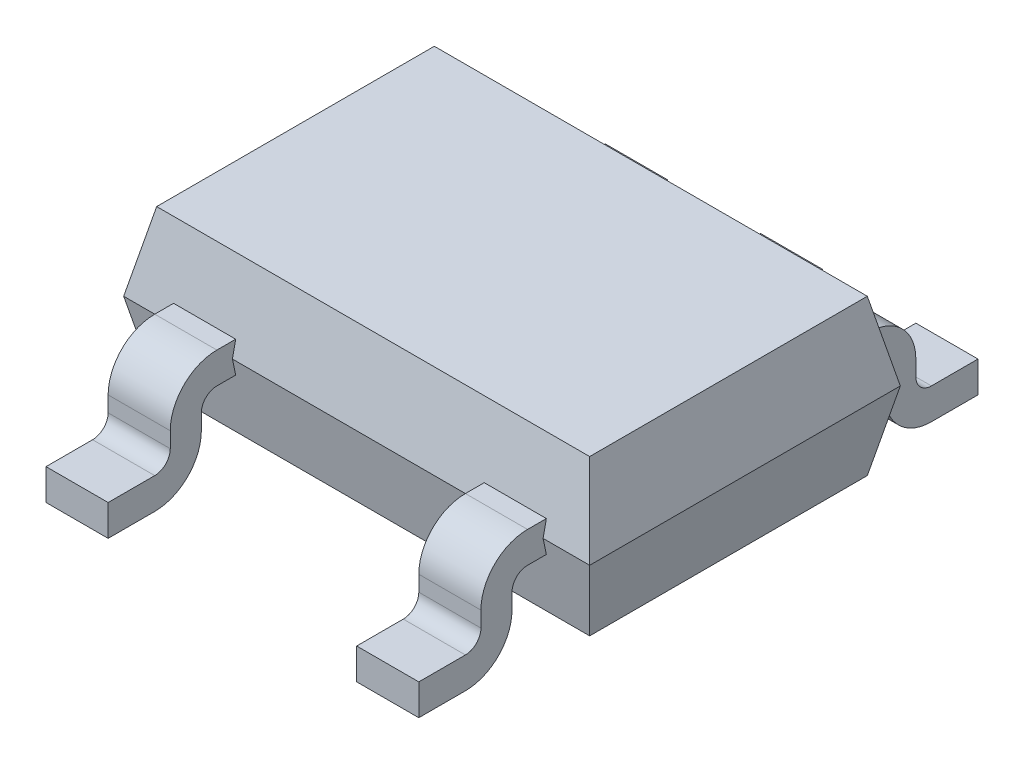
SolidWorks part; units mm, degrees
ref_plane "Front Plane" through (0, 0, 0) normal (0, 0, 1) x (1, 0, 0)
ref_plane "Top Plane" through (0, 0, 0) normal (0, 1, 0) x (1, 0, 0)
ref_plane "Right Plane" through (0, 0, 0) normal (1, 0, 0) x (0, 0, -1)
sketch "BaseS" plane through (0, 0, 0) normal (0, 1, 0) x (1, 0, 0)
  line L1 (-1.5, 1) -> (1.5, 1)
  line L2 (-1.5, 1) -> (-1.5, -1)
  line L3 (-1.5, -1) -> (1.5, -1)
  line L4 (1.5, 1) -> (1.5, -1)
  line L5 (-1.5, 1) -> (1.5, -1) construction
  line L6 (-1.5, -1) -> (1.5, 1) construction
  point P0 (0, 0)
  dimension "Width" = 3
  dimension "Length" = 2
extrude "Base" add sketch "BaseS" along normal mid plane 1 draft 12
sketch "VInSolderJointS" plane through (0, 0, 0) normal (1, 0, 0) x (0, 0, -1)
  line L0 (0.9, 0) -> (1.1, 0)
  line L1 (1.3, -0.2) -> (1.3, -0.3)
  line L2 (1.5, -0.5) -> (1.8, -0.5)
  line L3 (-0.8937, -0.5) -> (0.8937, -0.5) construction
  line L4 (0, -0.5) -> (0, 0) construction
  line L5 (-0.8937, -0.5) -> (0.8937, -0.5) construction
  line L6 (-1.5, -0.5) -> (-1.8, -0.5) construction
  line L7 (-1.3, -0.2) -> (-1.3, -0.3) construction
  line L8 (-0.9, 0) -> (-1.1, 0) construction
  arc A0 (1.1, 0) -> (1.3, -0.2) centre (1.1, -0.2) cw
  arc A1 (1.5, -0.5) -> (1.3, -0.3) centre (1.5, -0.3) cw
  arc A2 (-1.5, -0.5) -> (-1.3, -0.3) centre (-1.5, -0.3) ccw construction
  arc A3 (-1.1, 0) -> (-1.3, -0.2) centre (-1.1, -0.2) ccw construction
  point P3 (0, 0)
  dimension "Radius" = 0.2
  dimension "InnerLength" = 0.1
  dimension "TopOuterLength" = 0.1
  dimension "BottomLength" = 0.3
extrude "VInSolderJoint" add sketch "VInSolderJointS" along normal mid plane 0.4 thin thin type mid plane wall 0.2
pattern_linear "SJLP" count 2 spacing 1 along (1, 0, 0) count 2 spacing 1 along (-1, 0, 0) of "VInSolderJoint"
ref_plane "Plane1" through (1, 0, 0) normal (1, 0, 0) x (0, 0, -1)
sketch "VOutSolderJointS" plane through (1, 0, 0) normal (1, 0, 0) x (0, 0, -1)
  line L0 (-1.5, -0.5) -> (-1.8, -0.5) construction
  line L1 (-1.3, -0.2) -> (-1.3, -0.3) construction
  line L2 (-0.9, 0) -> (-1.1, 0) construction
  line L3 (-1.5, -0.5) -> (-1.8, -0.5)
  line L4 (-1.3, -0.2) -> (-1.3, -0.3)
  line L5 (-0.9, 0) -> (-1.1, 0)
  arc A0 (-1.5, -0.5) -> (-1.3, -0.3) centre (-1.5, -0.3) ccw construction
  arc A1 (-1.1, 0) -> (-1.3, -0.2) centre (-1.1, -0.2) ccw construction
  arc A2 (-1.5, -0.5) -> (-1.3, -0.3) centre (-1.5, -0.3) ccw
  arc A3 (-1.1, 0) -> (-1.3, -0.2) centre (-1.1, -0.2) ccw
extrude "VOutSolderJoint" add sketch "VOutSolderJointS" along normal mid plane 0.4 thin thin type mid plane wall 0.2
mirror "VOSJ HM" about plane through (0, 0, 0) normal (1, 0, 0) of "VOutSolderJoint"
equation "\"Width@VOutSolderJoint\"=\"Width@VInSolderJoint\""
equation "\"Height@VOutSolderJoint\"=\"Height@VInSolderJoint\""
